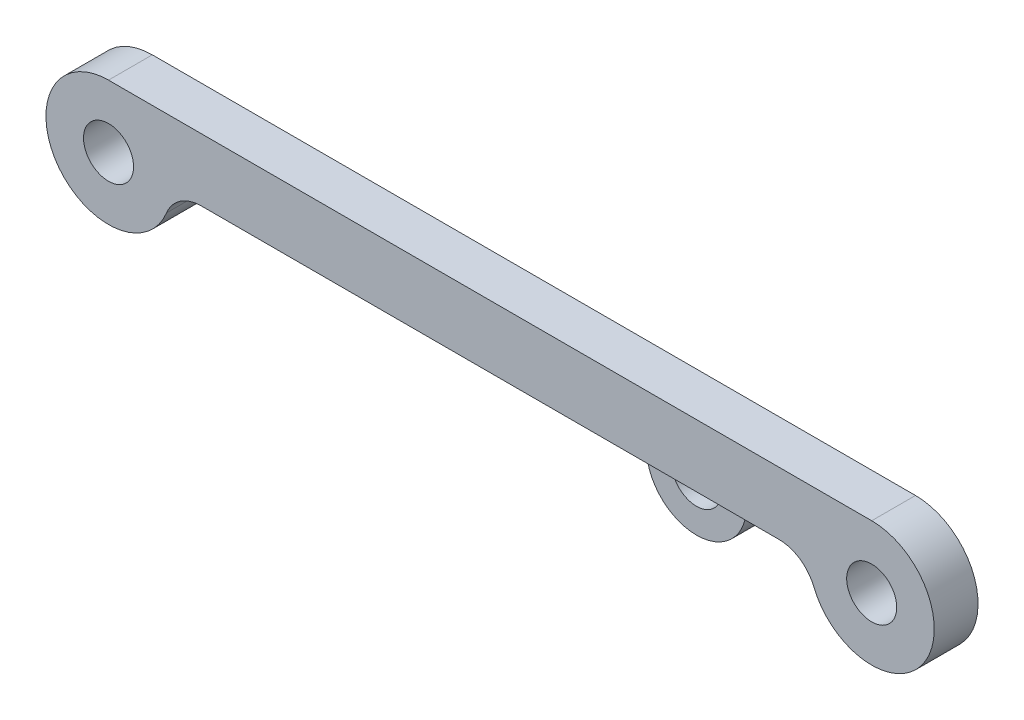
SolidWorks part; units mm, degrees
ref_plane "Front" through (0, 0, 0) normal (0, 0, 1) x (1, 0, 0)
ref_plane "Top" through (0, 0, 0) normal (0, 1, 0) x (1, 0, 0)
ref_plane "Right" through (0, 0, 0) normal (1, 0, 0) x (0, 0, -1)
sketch "Sketch1" plane through (0, 0, 0) normal (0, 0, 1) x (1, 0, 0)
  line L0 (-63.2211, 4.5) -> (-2.2211, 4.5)
  line L1 (-55.8049, -0.5) -> (-9.6373, -0.5)
  circle A0 centre (-63.2211, -0.5) radius 2
  circle A1 centre (-2.2211, -0.5) radius 2
  arc A2 (-63.2211, 4.5) -> (-58.586, -2.375) centre (-63.2211, -0.5) ccw
  arc A3 (-6.8563, -2.375) -> (-2.2211, 4.5) centre (-2.2211, -0.5) ccw
  arc A4 (-55.8049, -0.5) -> (-58.586, -2.375) centre (-55.8049, -3.5) ccw
  circle A5 centre (-63.2211, -0.5) radius 5 construction
  circle A6 centre (-2.2211, -0.5) radius 5 construction
  arc A7 (-9.6373, -0.5) -> (-6.8563, -2.375) centre (-9.6373, -3.5) cw
  point P5 (-6.7211, 0)
  point P12 (-58.7211, 0)
  point P16 (-58.2211, -0.5)
  dimension "D2" = 4
  dimension "D3" = 4
  dimension "D6" = 3
  dimension "D7" = 3
  dimension "D1" = 61
  dimension "D4" = 3
  dimension "D5" = 3
extrude "Boss-Extrude1" add sketch "Sketch1" along normal blind 3.5
sketch "Sketch3" plane through (0, 0, 3.5) normal (0, 0, 1) x (1, 0, 0)
  line L0 (-55.8049, -0.5) -> (-9.6373, -0.5) construction
  line L1 (-21.1272, -1.3617) -> (-19.026, -1.3617)
  line L2 (-21.2211, -0.5) -> (-19.2211, -0.5)
  arc A0 (-19.026, -1.3617) -> (-19.2211, -0.5) centre (-17.2211, -0.5) ccw
  arc A1 (-21.1272, -1.3617) -> (-21.2211, -0.5) centre (-17.2211, -0.5) ccw
  circle A2 centre (-2.2211, -0.5) radius 2 construction
  dimension "D1" = 4
  dimension "D2" = 8
  dimension "D3" = 15
extrude "Boss-Extrude3" add sketch "Sketch3" against normal blind 2 from offset 1 offset against normal yes
fillet "Fillet1" radius 1 1 edges at (-13.2211, -0.5, 1.5)
